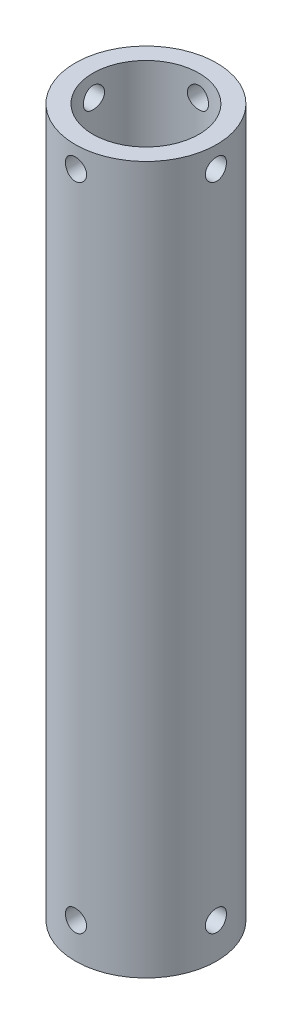
SolidWorks part; units mm, degrees
material "1060 Alloy"
ref_plane "Front Plane" through (0, 0, 0) normal (0, 0, 1) x (1, 0, 0)
ref_plane "Top Plane" through (0, 0, 0) normal (0, 1, 0) x (1, 0, 0)
ref_plane "Right Plane" through (0, 0, 0) normal (1, 0, 0) x (0, 0, -1)
sketch "Sketch1" plane through (0, 0, 0) normal (0, 1, 0) x (1, 0, 0)
  line L0 (0, 0) -> (-12.7, 0) construction
  circle A0 centre (0, 0) radius 12.7
  circle A1 centre (0, 0) radius 9.525
  dimension "D1" = 25.4
  dimension "D2" = 19.05
extrude "ElTubo" add sketch "Sketch1" along normal blind 127
ref_plane "Plane1" through (-12.7, 0, 0) normal (-1, 0, 0) x (0, 0, 1)
sketch "HoleLocator" plane through (-12.7, 0, 0) normal (-1, 0, 0) x (0, 0, 1)
  line L0 (0, 0) -> (0, 6.35) construction
  line L1 (0, 6.35) -> (0, 123.19) construction
  point P0 (0, 0)
  point P9 (0, 123.19)
  point P12 (0, 6.35)
  dimension "D1" = 6.35
hole_wizard "SetScrew" positions "HoleLocator" profile "Sketch3" hole size "#10-24" standard "ANSI Inch"
sketch "Sketch3" plane through (-12.7, 6.35, 0) normal (0, 1, 0) x (0, 0, 1)
  line L0 (0, 0) -> (0, 3.175)
  line L1 (0, 3.175) -> (1.8986, 3.175)
  line L2 (1.8986, 3.175) -> (1.8986, 0)
  line L5 (1.8986, 0) -> (0, 0)
  line L11 (0, -6.35) -> (0, 107.95) construction
  dimension "Thru Hole Dia." = 3.7973
  dimension "Thru Hole Depth" = 3.175
pattern_circular "CirPattern1" count 4 over 360 about axis through (0, 127, 0) along (0, -1, 0) of "SetScrew"
